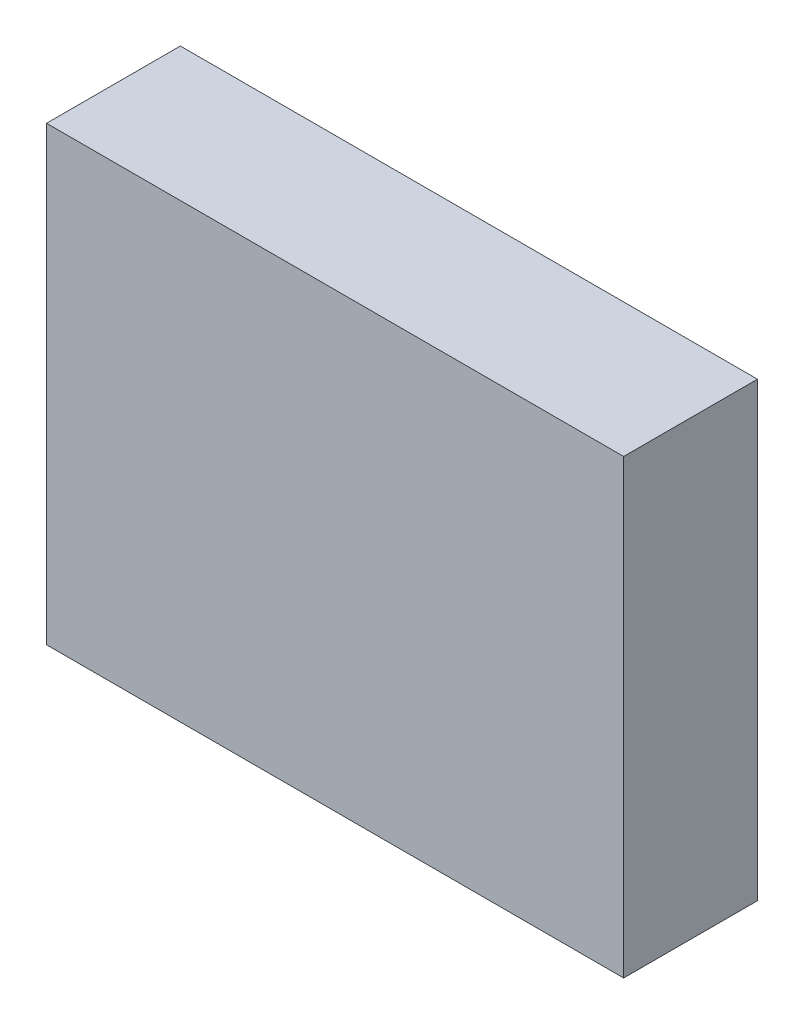
SolidWorks part; units mm, degrees
ref_plane "Front Plane" through (0, 0, 0) normal (0, 0, 1) x (1, 0, 0)
ref_plane "Top Plane" through (0, 0, 0) normal (0, 1, 0) x (1, 0, 0)
ref_plane "Right Plane" through (0, 0, 0) normal (1, 0, 0) x (0, 0, -1)
sketch "Sketch1" plane through (0, 0, 0) normal (0, 0, 1) x (1, 0, 0)
  line L1 (0, 0) -> (69, 0)
  line L2 (0, 0) -> (0, 54)
  line L3 (0, 54) -> (69, 54)
  line L4 (69, 0) -> (69, 54)
  dimension "D1" = 69
  dimension "D2" = 54
extrude "Profile" add sketch "Sketch1" along normal blind 16
equation "\"Profile_Depth\" = 16mm"
equation "\"D1@Profile\" = \"Profile_Depth\""
equation "\"EnvelopeWidth\" = 69mm"
equation "\"EnvelopeHeight\" = 54mm"
